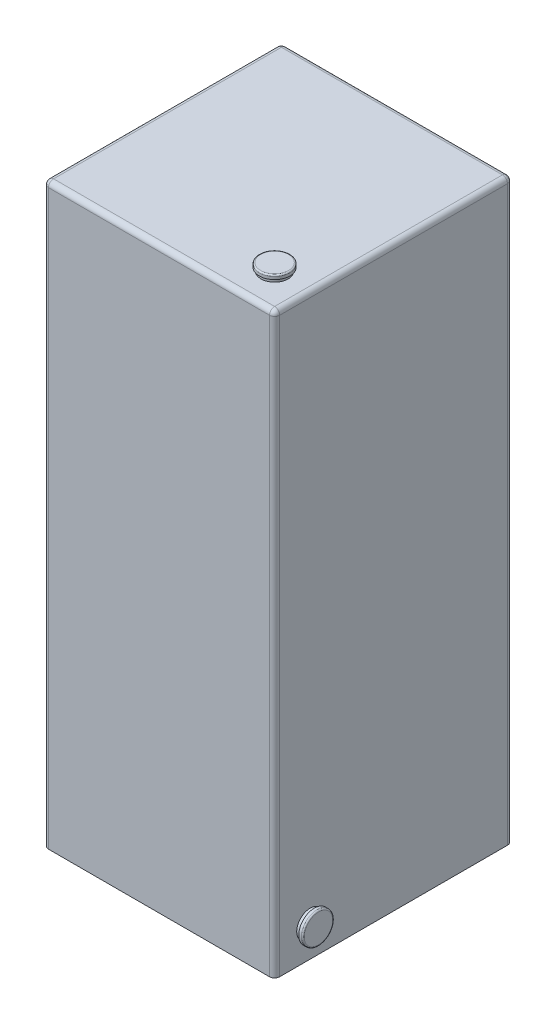
SolidWorks part; units mm, degrees
ref_plane "Alzado" through (0, 0, 0) normal (0, 0, 1) x (1, 0, 0)
ref_plane "Planta" through (0, 0, 0) normal (0, 1, 0) x (1, 0, 0)
ref_plane "Vista lateral" through (0, 0, 0) normal (1, 0, 0) x (0, 0, -1)
sketch "Croquis1" plane through (0, 0, 0) normal (0, 0, 1) x (1, 0, 0)
  line L1 (0, 0) -> (680, 0)
  line L2 (0, 0) -> (0, 1700)
  line L3 (0, 1700) -> (680, 1700)
  line L4 (680, 0) -> (680, 1700)
  dimension "D1" = 1700
  dimension "D2" = 680
extrude "Saliente-Extruir1" add sketch "Croquis1" along normal blind 700
fillet "Redondeo1" radius 15 8 edges at (0, 850, 0) (680, 850, 0) (340, 1700, 0) (0, 850, 700) (680, 850, 700) (680, 1700, 350) (0, 1700, 350) (340, 1700, 700)
sketch "Croquis4" plane through (0, 1700, 0) normal (0, 1, 0) x (1, 0, 0)
  line L0 (15, -685) -> (665, -685) construction
  line L1 (665, -685) -> (665, -15) construction
  circle A0 centre (575, -595) radius 40
  dimension "D1" = 80
  dimension "D2" = 90
  dimension "D3" = 90
extrude "Saliente-Extruir4" add sketch "Croquis4" along normal blind 22
sketch "Croquis5" plane through (0, 1722, 0) normal (0, 1, 0) x (1, 0, 0)
  circle A0 centre (575, -595) radius 45
  dimension "D1" = 90
extrude "Saliente-Extruir5" add sketch "Croquis5" against normal blind 12
fillet "Redondeo3" radius 4 1 edges at (575, 1722, 640)
sketch "Croquis6" plane through (680, 0, 0) normal (1, 0, 0) x (0, 0, -1)
  line L0 (-685, 1685) -> (-685, 0) construction
  line L1 (-685, 0) -> (-15, 0) construction
  circle A0 centre (-595, 90) radius 40
  dimension "D1" = 80
  dimension "D2" = 90
  dimension "D3" = 90
extrude "Saliente-Extruir6" add sketch "Croquis6" along normal blind 24
sketch "Croquis7" plane through (704, 0, 0) normal (1, 0, 0) x (0, 0, -1)
  circle A0 centre (-595, 90) radius 46
  dimension "D1" = 92
extrude "Saliente-Extruir7" add sketch "Croquis7" against normal blind 12
fillet "Redondeo5" radius 4 1 edges at (704, 90, 549)
